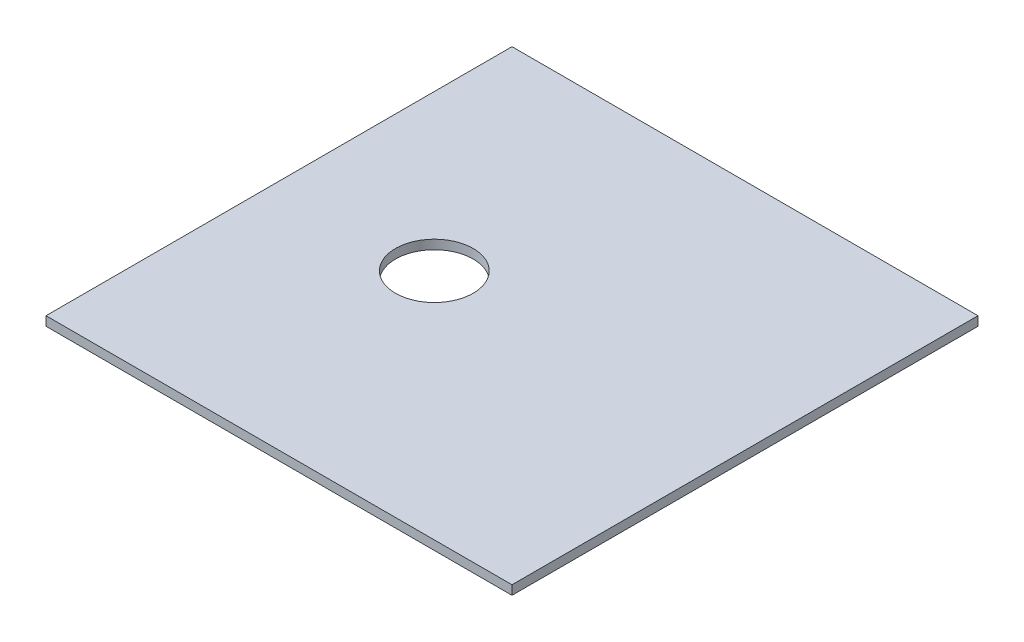
SolidWorks part; units mm, degrees
ref_plane "Front Plane" through (0, 0, 0) normal (0, 0, 1) x (1, 0, 0)
ref_plane "Top Plane" through (0, 0, 0) normal (0, 1, 0) x (1, 0, 0)
ref_plane "Right Plane" through (0, 0, 0) normal (1, 0, 0) x (0, 0, -1)
sketch "Sketch1" plane through (0, 0, 0) normal (0, 1, 0) x (1, 0, 0)
  line L0 (-76.2, 0) -> (-25.4, 0) construction
  line L1 (-76.2, 76.2) -> (76.2, 76.2)
  line L2 (-76.2, 76.2) -> (-76.2, -76.2)
  line L3 (-76.2, -76.2) -> (76.2, -76.2)
  line L4 (76.2, 76.2) -> (76.2, -76.2)
  line L5 (-76.2, 76.2) -> (76.2, -76.2) construction
  line L6 (-76.2, -76.2) -> (76.2, 76.2) construction
  circle A0 centre (-25.4, 0) radius 12.7
  circle A1 centre (-57.5137, -57.5137) radius 5
  circle A2 centre (-57.5137, 57.5137) radius 5
  circle A3 centre (57.5137, 57.5137) radius 5
  circle A4 centre (57.5137, -57.5137) radius 5
  point P0 (0, 0)
  point P20 (0, 0)
  dimension "D4" = 25.4
  dimension "D5" = 10
  dimension "D1" = 152.4
  dimension "D2" = 152.4
  dimension "D3" = 50.8
  dimension "D6" = 4
extrude "Boss-Extrude1" add sketch "Sketch1" against normal blind 3 contours A1 | A4 | L4 L1 L2 L3 A4 A3 A2 A1 A0 | A3 | A2
